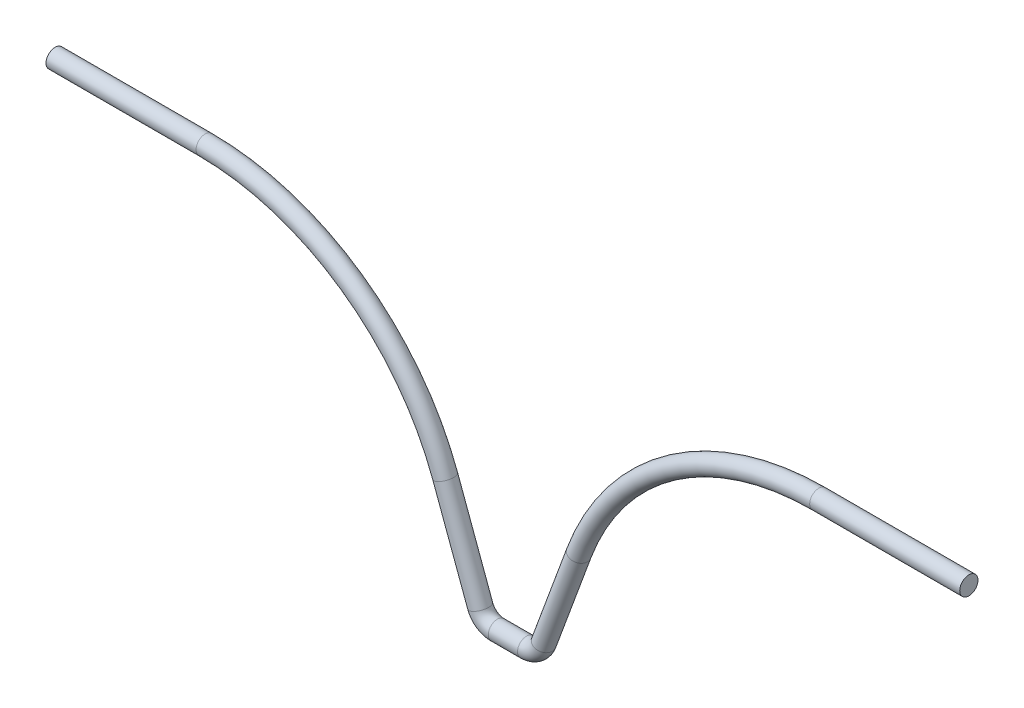
SolidWorks part; units mm, degrees
ref_plane "Front Plane" through (0, 0, 0) normal (0, 0, 1) x (1, 0, 0)
ref_plane "Top Plane" through (0, 0, 0) normal (0, 1, 0) x (1, 0, 0)
ref_plane "Right Plane" through (0, 0, 0) normal (1, 0, 0) x (0, 0, -1)
sketch "Sketch1" plane through (0, 0, 0) normal (0, 0, 1) x (1, 0, 0)
  line L0 (0, 69.353) -> (0, 104.0989) construction
  line L1 (4, 69.353) -> (-4, 69.353)
  line L2 (-8.6907, 72.6216) -> (-18.2766, 98.5922)
  line L3 (-83.946, 144.353) -> (-125, 144.353)
  line L4 (83.946, 144.353) -> (125, 144.353)
  line L5 (8.6907, 72.6216) -> (18.2766, 98.5922)
  line L6 (0, 69.353) -> (-137.3327, 69.353) construction
  arc A0 (-18.2766, 98.5922) -> (-83.946, 144.353) centre (-83.946, 74.353) ccw
  arc A1 (-4, 69.353) -> (-8.6907, 72.6216) centre (-4, 74.353) cw
  arc A2 (4, 69.353) -> (8.6907, 72.6216) centre (4, 74.353) ccw
  arc A3 (18.2766, 98.5922) -> (83.946, 144.353) centre (83.946, 74.353) cw
  dimension "D3" = 75
  dimension "D4" = 5
  dimension "D5" = 70
  dimension "D6" = 5
  dimension "D1" = 125
  dimension "D2" = 8
sweep "Sweep1" add path "Sketch1" circular profile diameter 5 parameters "D3"=5
